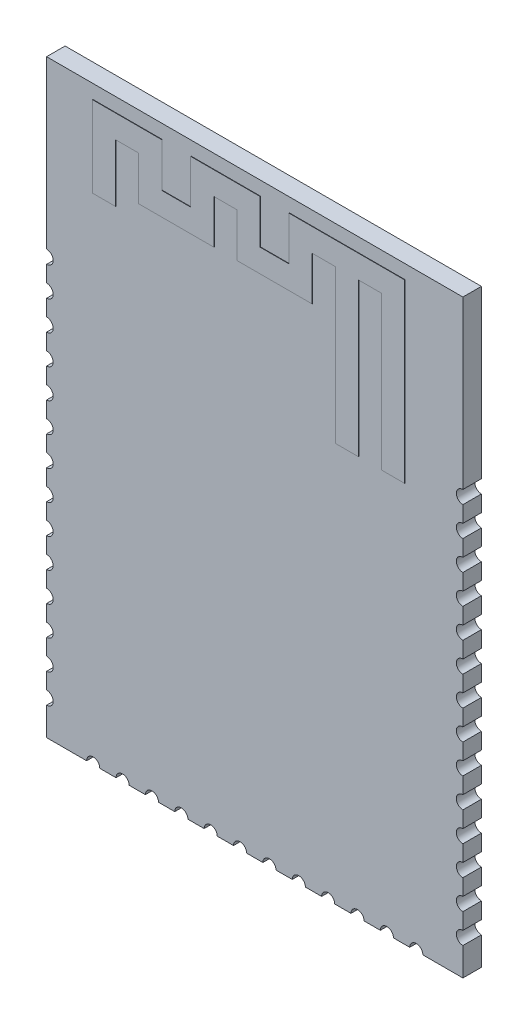
SolidWorks part; units mm, degrees
ref_plane "Přední rovina" through (0, 0, 0) normal (0, 0, 1) x (1, 0, 0)
ref_plane "Horní rovina" through (0, 0, 0) normal (0, 1, 0) x (1, 0, 0)
ref_plane "Pravá rovina" through (0, 0, 0) normal (1, 0, 0) x (0, 0, -1)
sketch "Skica1" plane through (0, 0, 0) normal (0, 0, 1) x (1, 0, 0)
  line L1 (9, -9.6) -> (-9, -9.6)
  line L2 (9, -9.6) -> (9, 9.6)
  line L3 (9, 9.6) -> (-9, 9.6)
  line L4 (-9, -9.6) -> (-9, 9.6)
  line L5 (9, -9.6) -> (-9, 9.6) construction
  line L6 (9, 9.6) -> (-9, -9.6) construction
  point P0 (0, 0)
  dimension "D1" = 18
  dimension "D2" = 19.2
extrude "body_small" add sketch "Skica1" along normal blind 0.8
sketch "Skica2" plane through (0, 0, 0) normal (0, 0, -1) x (-1, 0, 0)
  line L0 (-9, 9.6) -> (9, 9.6) construction
  line L1 (9, 9.6) -> (-9, 9.6)
  line L2 (9, 9.6) -> (9, 15.9)
  line L3 (9, 15.9) -> (-9, 15.9)
  line L4 (-9, 9.6) -> (-9, 15.9)
  line L5 (9, -9.6) -> (-9, -9.6) construction
  dimension "D1" = 25.5
extrude "body_extension" add sketch "Skica2" against normal up to surface (0.8 mm away) up to face at (0, 0, 0.8)
sketch "Skica3" plane through (0, 0, 0.8) normal (0, 0, 1) x (1, 0, 0)
  line L0 (-9, -9.6) -> (9, -9.6) construction
  line L1 (-9, 15.9) -> (-9, -9.6) construction
  line L2 (9, -9.6) -> (9, 15.9) construction
  line L3 (-9, -8.1) -> (-9, -6.83) construction
  line L4 (-6.985, -9.6) -> (-5.715, -9.6) construction
  line L5 (-0.635, -9.6) -> (0, -9.6) construction
  line L6 (0, -9.6) -> (0.635, -9.6) construction
  line L7 (0, -9.6) -> (0, 0) construction
  circle A0 centre (-6.985, -9.6) radius 0.284
  circle A1 centre (-9, -8.1) radius 0.284
  circle A2 centre (9, -8.1) radius 0.284
  circle A3 centre (-9, -6.83) radius 0.284
  circle A4 centre (9, -6.83) radius 0.284
  circle A5 centre (-9, -5.56) radius 0.284
  circle A6 centre (9, -5.56) radius 0.284
  circle A7 centre (-9, -4.29) radius 0.284
  circle A8 centre (9, -4.29) radius 0.284
  circle A9 centre (-9, -3.02) radius 0.284
  circle A10 centre (9, -3.02) radius 0.284
  circle A11 centre (-9, -1.75) radius 0.284
  circle A12 centre (9, -1.75) radius 0.284
  circle A13 centre (-9, -0.48) radius 0.284
  circle A14 centre (9, -0.48) radius 0.284
  circle A15 centre (-9, 0.79) radius 0.284
  circle A16 centre (9, 0.79) radius 0.284
  circle A17 centre (-9, 2.06) radius 0.284
  circle A18 centre (9, 2.06) radius 0.284
  circle A19 centre (-9, 3.33) radius 0.284
  circle A20 centre (9, 3.33) radius 0.284
  circle A21 centre (-9, 4.6) radius 0.284
  circle A22 centre (9, 4.6) radius 0.284
  circle A23 centre (-9, 5.87) radius 0.284
  circle A24 centre (9, 5.87) radius 0.284
  circle A25 centre (-9, 7.14) radius 0.284
  circle A26 centre (9, 7.14) radius 0.284
  circle A27 centre (-9, 8.41) radius 0.284
  circle A28 centre (9, 8.41) radius 0.284
  circle A29 centre (-5.715, -9.6) radius 0.284
  circle A30 centre (-4.445, -9.6) radius 0.284
  circle A31 centre (-3.175, -9.6) radius 0.284
  circle A32 centre (-1.905, -9.6) radius 0.284
  circle A33 centre (-0.635, -9.6) radius 0.284
  circle A34 centre (0.635, -9.6) radius 0.284
  circle A35 centre (1.905, -9.6) radius 0.284
  circle A36 centre (3.175, -9.6) radius 0.284
  circle A37 centre (4.445, -9.6) radius 0.284
  circle A38 centre (5.715, -9.6) radius 0.284
  circle A39 centre (6.985, -9.6) radius 0.284
  dimension "D6" = 0.568
  dimension "D2" = 1.27
  dimension "D4" = 1.27
  dimension "D5" = 13.97
  dimension "D7" = 16.51
  dimension "D8" = 1.5
  dimension "D1" = 14
  dimension "D3" = 12
extrude "vias" cut sketch "Skica3" against normal through all
sketch "Skica4" plane through (0, 0, 0.8) normal (0, 0, 1) x (1, 0, 0)
  line L0 (-7, 11.8) -> (-6, 11.8)
  line L1 (-6, 11.8) -> (-6, 14.3)
  line L2 (-6, 14.3) -> (-5, 14.3)
  line L3 (-5, 14.3) -> (-5, 12.4)
  line L4 (-5, 12.4) -> (-1.75, 12.4)
  line L5 (-1.75, 12.4) -> (-1.75, 14.3)
  line L6 (-1.75, 14.3) -> (-0.75, 14.3)
  line L7 (-0.75, 14.3) -> (-0.75, 12.4)
  line L8 (-0.75, 12.4) -> (2.5, 12.4)
  line L9 (2.5, 12.4) -> (2.5, 14.3)
  line L10 (2.5, 14.3) -> (3.5, 14.3)
  line L11 (3.5, 14.3) -> (3.5, 7.68)
  line L12 (3.5, 7.68) -> (4.5, 7.68)
  line L13 (4.5, 7.68) -> (4.5, 14.3)
  line L14 (4.5, 14.3) -> (5.5, 14.3)
  line L15 (5.5, 14.3) -> (5.5, 7.68)
  line L16 (5.5, 7.68) -> (6.5, 7.68)
  line L17 (6.5, 7.68) -> (6.5, 15.3)
  line L18 (6.5, 15.3) -> (1.5, 15.3)
  line L19 (1.5, 15.3) -> (1.5, 13.4)
  line L20 (1.5, 13.4) -> (0.25, 13.4)
  line L21 (0.25, 13.4) -> (0.25, 15.3)
  line L22 (0.25, 15.3) -> (-2.75, 15.3)
  line L23 (-2.75, 15.3) -> (-2.75, 13.4)
  line L24 (-2.75, 13.4) -> (-4, 13.4)
  line L25 (-4, 13.4) -> (-4, 15.3)
  line L26 (-4, 15.3) -> (-7, 15.3)
  line L27 (-7, 15.3) -> (-7, 11.8)
  line L28 (-9, 15.9) -> (-9, 8.694) construction
  line L29 (9, 8.694) -> (9, 15.9) construction
  line L30 (-9, 15.9) -> (9, 15.9) construction
  dimension "D1" = 2
  dimension "D2" = 2.5
  dimension "D3" = 5
  dimension "D4" = 3
  dimension "D5" = 3
  dimension "D6" = 1
  dimension "D7" = 3.5
  dimension "D8" = 0.6
  dimension "D9" = 1
  dimension "D10" = 1.9
  dimension "D11" = 1
  dimension "D12" = 7.62
extrude "antenna" add sketch "Skica4" along normal blind 0.018
